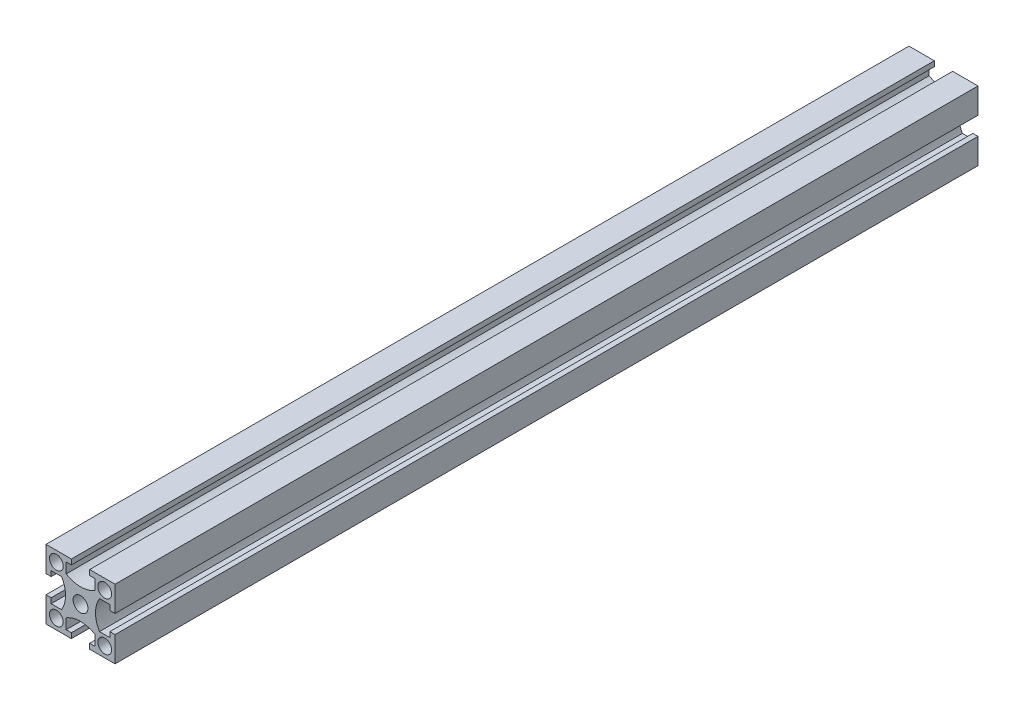
SolidWorks part; units mm, degrees
ref_plane "정면" through (0, 0, 0) normal (0, 0, 1) x (1, 0, 0)
ref_plane "윗면" through (0, 0, 0) normal (0, 1, 0) x (1, 0, 0)
ref_plane "우측면" through (0, 0, 0) normal (1, 0, 0) x (0, 0, -1)
sketch "스케치1" plane through (0, 0, 0) normal (0, 0, 1) x (1, 0, 0)
  line L1 (-10, 10) -> (10, 10)
  line L2 (-10, 10) -> (-10, -10)
  line L3 (-10, -10) -> (10, -10)
  line L4 (10, 10) -> (10, -10)
  line L5 (-10, 10) -> (10, -10) construction
  line L6 (-10, -10) -> (10, 10) construction
  point P0 (0, 0)
  dimension "D1" = 20
  dimension "D2" = 20
extrude "보스-돌출1" add sketch "스케치1" along normal blind 250
sketch "스케치2" plane through (0, 0, 250) normal (0, 0, 1) x (1, 0, 0)
  line L0 (-2.65, 10) -> (-2.65, 8.5)
  line L1 (10, 10) -> (-10, 10) construction
  line L2 (-2.65, 8.5) -> (-4.15, 8.5)
  line L3 (-4.15, 8.5) -> (-4.15, 5.5)
  line L4 (-2.65, 10) -> (2.65, 10)
  line L5 (2.65, 10) -> (2.65, 8.5)
  line L6 (2.65, 8.5) -> (4.15, 8.5)
  line L7 (4.15, 8.5) -> (4.15, 5.5)
  line L8 (10, 2.65) -> (8.5, 2.65)
  line L9 (8.5, 2.65) -> (8.5, 4.15)
  line L10 (8.5, 4.15) -> (5.5, 4.15)
  line L11 (10, 2.65) -> (10, -2.65)
  line L12 (10, -2.65) -> (8.5, -2.65)
  line L13 (8.5, -2.65) -> (8.5, -4.15)
  line L14 (8.5, -4.15) -> (5.5, -4.15)
  line L15 (2.65, -10) -> (2.65, -8.5)
  line L16 (2.65, -8.5) -> (4.15, -8.5)
  line L17 (4.15, -8.5) -> (4.15, -5.5)
  line L18 (2.65, -10) -> (-2.65, -10)
  line L19 (-2.65, -10) -> (-2.65, -8.5)
  line L20 (-2.65, -8.5) -> (-4.15, -8.5)
  line L21 (-4.15, -8.5) -> (-4.15, -5.5)
  line L22 (-10, -2.65) -> (-8.5, -2.65)
  line L23 (-8.5, -2.65) -> (-8.5, -4.15)
  line L24 (-8.5, -4.15) -> (-5.5, -4.15)
  line L25 (-10, -2.65) -> (-10, 2.65)
  line L26 (-10, 2.65) -> (-8.5, 2.65)
  line L27 (-8.5, 2.65) -> (-8.5, 4.15)
  line L28 (-8.5, 4.15) -> (-5.5, 4.15)
  arc A1 (-4.15, 5.5) -> (4.15, 5.5) centre (0, 12.3394) ccw
  arc A2 (5.5, 4.15) -> (5.5, -4.15) centre (12.3394, 0) ccw
  arc A3 (4.15, -5.5) -> (-4.15, -5.5) centre (0, -12.3394) ccw
  arc A4 (-5.5, -4.15) -> (-5.5, 4.15) centre (-12.3394, 0) ccw
  circle A5 centre (0, 0) radius 2.15
  circle A6 centre (-7, 7) radius 2
  circle A7 centre (7, 7) radius 2
  circle A8 centre (7, -7) radius 2
  circle A9 centre (-7, -7) radius 2
  point P4 (-2.65, 9.25)
  point P43 (0, 0)
  dimension "D2" = 1.5
  dimension "D8" = 4.3
  dimension "D9" = 4
  dimension "D10" = 4
  dimension "D11" = 4
  dimension "D12" = 4
  dimension "D21" = 8
  dimension "D1" = 5.3
  dimension "D3" = 8.3
  dimension "D4" = 4.15
  dimension "D5" = 2.65
  dimension "D6" = 4
  dimension "D7" = 3
  dimension "D13" = 14
  dimension "D14" = 7
  dimension "D15" = 7
  dimension "D16" = 7
  dimension "D17" = 14
  dimension "D18" = 7
  dimension "D19" = 7
  dimension "D20" = 7
extrude "컷-돌출1" cut sketch "스케치2" against normal blind 300
sketch "스케치3" plane through (10, 0, 0) normal (1, 0, 0) x (0, 0, -1)
  line L0 (-250, 10) -> (0, 10) construction
  line L1 (-179.9666, 10) -> (-186.8217, 10)
  line L2 (-179.9666, 10) -> (-179.9666, 5.7908)
  line L3 (-179.9666, 5.7908) -> (-186.8217, 5.7908)
  line L4 (-186.8217, 10) -> (-186.8217, 5.7908)
  line L6 (-153.6429, 10) -> (-160.498, 10)
  line L7 (-153.6429, 10) -> (-153.6429, 5.7908)
  line L8 (-153.6429, 5.7908) -> (-160.498, 5.7908)
  line L9 (-160.498, 10) -> (-160.498, 5.7908)
  line L10 (-46.1547, 10) -> (-52.7356, 10)
  line L11 (-46.1547, 10) -> (-46.1547, 5.7908)
  line L12 (-46.1547, 5.7908) -> (-52.7356, 5.7908)
  line L13 (-52.7356, 10) -> (-52.7356, 5.7908)
  line L14 (-19.5568, 10) -> (-27.5088, 10)
  line L15 (-19.5568, 10) -> (-19.5568, 5.7908)
  line L16 (-19.5568, 5.7908) -> (-27.5088, 5.7908)
  line L17 (-27.5088, 10) -> (-27.5088, 5.7908)
